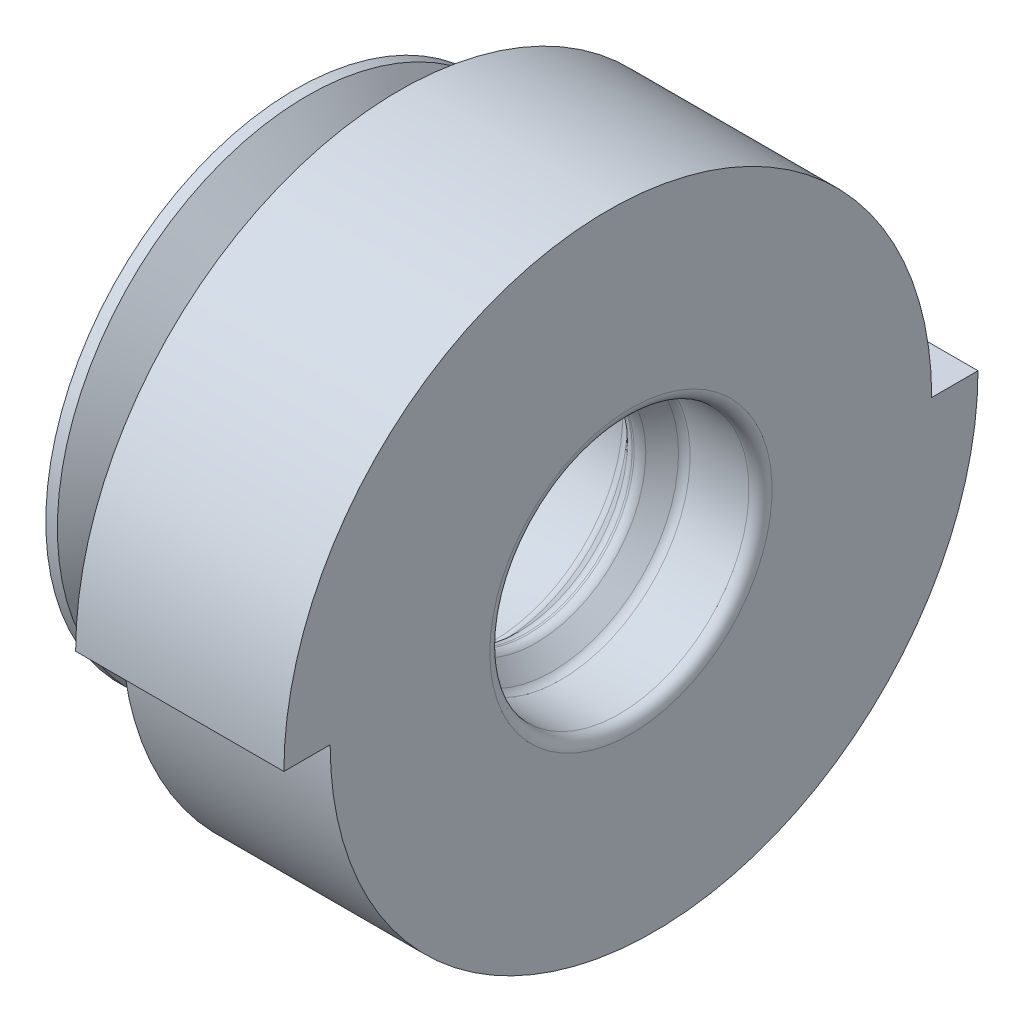
SolidWorks part; units mm, degrees
ref_plane "Front Plane" through (0, 0, 0) normal (0, 0, 1) x (1, 0, 0)
ref_plane "Top Plane" through (0, 0, 0) normal (0, 1, 0) x (1, 0, 0)
ref_plane "Right Plane" through (0, 0, 0) normal (1, 0, 0) x (0, 0, -1)
sketch "Sketch1" plane through (0, 0, 0) normal (1, 0, 0) x (0, 0, -1)
  line L2 (26, 0) -> (30, 0)
  line L3 (-26, 0) -> (-30, 0)
  circle A0 centre (0, 0) radius 11.2
  circle A1 centre (0, 0) radius 30 construction
  circle A2 centre (0, 0) radius 26 construction
  arc A5 (30, 0) -> (-26, 0) centre (2, 0) cw
  arc A6 (-30, 0) -> (26, 0) centre (-2, 0) cw
  dimension "D1" = 22.4
  dimension "D2" = 60
  dimension "D3" = 52
extrude "Boss-Extrude1" add sketch "Sketch1" along normal blind 18
sketch "Sketch2" plane through (0, 0, 0) normal (0, 1, 0) x (1, 0, 0)
  line L0 (0, 21.5794) -> (-1, 21.5794)
  line L2 (-1, 21.5794) -> (-1, 18.6)
  line L3 (-1, 18.6) -> (-7.5, 18.6)
  line L4 (-7.5, 18.6) -> (-10, 21.5794)
  line L5 (-10, 21.5794) -> (-11, 21.5794)
  line L6 (-11, 21.5794) -> (-11, 17.5794)
  line L7 (-11, 17.5794) -> (0, 11.2)
  line L8 (0, 11.2) -> (0, 21.5794)
  line L11 (0, 0) -> (-24.615, 0) construction
  dimension "D1" = 21.5794
  dimension "D2" = 4
  dimension "D3" = 6.5
  dimension "D4" = 18.6
  dimension "D5" = 1
  dimension "D6" = 50
revolve "Revolve1" add sketch "Sketch2" angle 360 about L11
sketch "Sketch4" plane through (0, 0, 0) normal (0, 0, 1) x (1, 0, 0)
  line L0 (6.5, 11.2) -> (8.5, 9.2)
  line L1 (8.5, 9.2) -> (9.5, 9.2)
  line L2 (9.5, 9.2) -> (11.5, 11.2)
  line L3 (11.5, 11.2) -> (6.5, 11.2)
  line L6 (18, 11.2) -> (0, 11.2) construction
  line L7 (-0.5, -28.1614) -> (18.5, -28.1614) construction
  line L9 (0, 0) -> (18, 0) construction
  point P4 (9, -28.1614)
  point P12 (9, 9.2)
  point P13 (9, 0)
  point P17 (9, 11.2)
  dimension "D1" = 45
  dimension "D2" = 19
  dimension "D3" = 7
  dimension "D4" = 2
revolve "Revolve2" add sketch "Sketch4" angle 360 about L9
fillet "Fillet1" radius 1 7 edges at (9.5, 0, 9.2) (11.5, 0, 11.2) (6.5, 0, 11.2) (0, 0, -11.2) (-11, 0, -17.5794) (8.5, 0, 9.2) (18, 0, -11.2)
